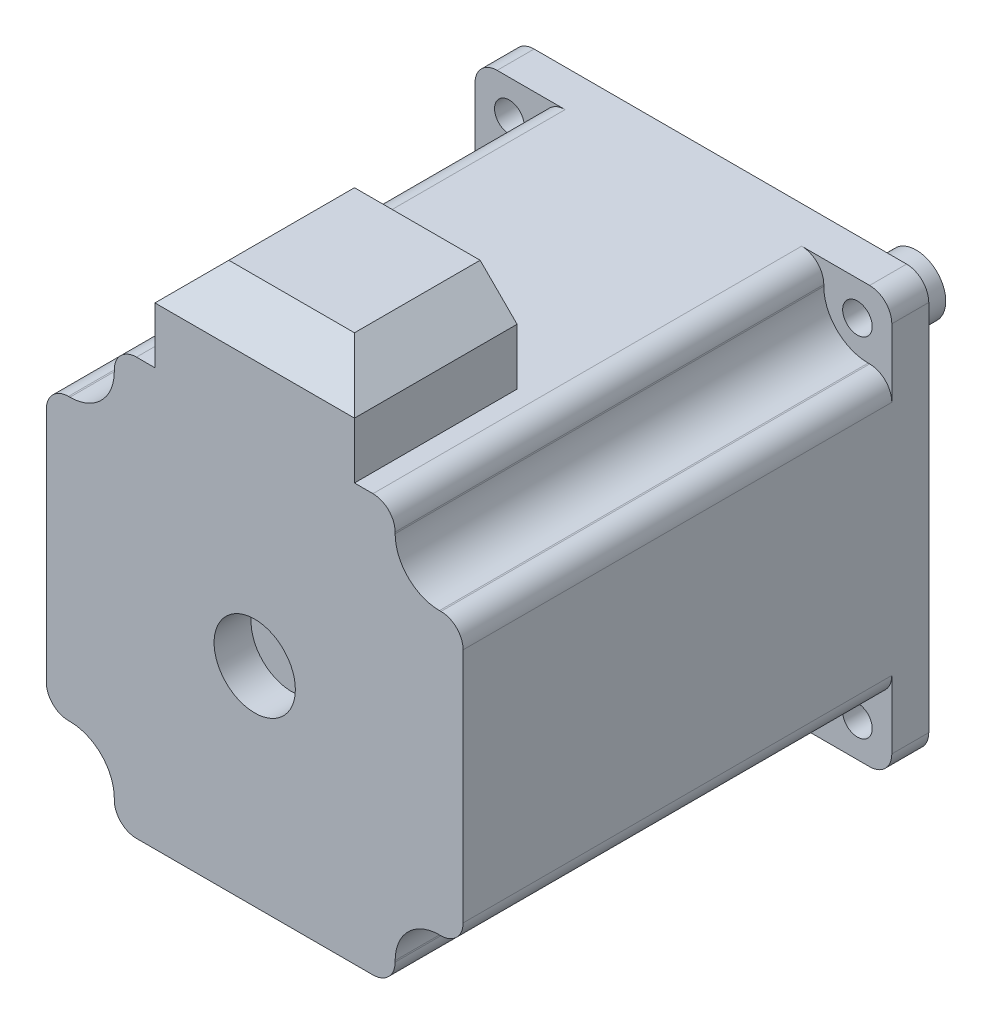
SolidWorks part; units mm, degrees
ref_plane "前视基准面" through (0, 0, 0) normal (0, 0, 1) x (1, 0, 0)
ref_plane "上视基准面" through (0, 0, 0) normal (0, 1, 0) x (1, 0, 0)
ref_plane "右视基准面" through (0, 0, 0) normal (1, 0, 0) x (0, 0, -1)
sketch "草图1" plane through (0, 0, 0) normal (0, 0, 1) x (1, 0, 0)
  line L1 (-28.2, 28.2) -> (28.2, 28.2)
  line L2 (-28.2, 28.2) -> (-28.2, -28.2)
  line L3 (-28.2, -28.2) -> (28.2, -28.2)
  line L4 (28.2, 28.2) -> (28.2, -28.2)
  line L5 (-28.2, 28.2) -> (28.2, -28.2) construction
  line L6 (-28.2, -28.2) -> (28.2, 28.2) construction
  point P0 (0, 0)
  dimension "D1" = 56.4
  dimension "D2" = 56.4
extrude "凸台-拉伸1" add sketch "草图1" along normal blind 63
sketch "草图2" plane through (0, 0, 0) normal (0, 0, -1) x (-1, 0, 0)
  line L0 (0, 0) -> (0, 23.55) construction
  line L1 (-23.55, 23.55) -> (23.55, 23.55) construction
  line L2 (-23.55, 23.55) -> (-23.55, -23.55) construction
  line L3 (-23.55, -23.55) -> (23.55, -23.55) construction
  line L4 (23.55, 23.55) -> (23.55, -23.55) construction
  circle A0 centre (23.55, 23.55) radius 2
  circle A1 centre (23.55, -23.55) radius 2
  circle A2 centre (-23.55, -23.55) radius 2
  circle A3 centre (-23.55, 23.55) radius 2
  point P0 (0, 0)
  dimension "D1" = 47.1
  dimension "D2" = 47.1
extrude "切除-拉伸1" cut sketch "草图2" against normal blind 63
sketch "草图3" plane through (0, 0, 63) normal (0, 0, 1) x (1, 0, 0)
  line L0 (28.2, -28.2) -> (28.2, 28.2) construction
  line L1 (-19, -28.2) -> (19, -28.2) construction
  line L2 (-19, -28.2) -> (-19, -19)
  line L3 (-19, 28.2) -> (19, 28.2) construction
  line L4 (19, -28.2) -> (19, -19)
  line L5 (-28.2, -19) -> (-28.2, -28.2)
  line L6 (-28.2, -28.2) -> (-19, -28.2)
  line L7 (-28.2, 19) -> (-19, 19)
  line L8 (-28.2, 19) -> (-28.2, -19) construction
  line L9 (-28.2, -19) -> (-19, -19)
  line L10 (28.2, 19) -> (28.2, -19) construction
  line L11 (28.2, -19) -> (28.2, -28.2)
  line L12 (28.2, -28.2) -> (19, -28.2)
  line L13 (19, 19) -> (28.2, 19)
  line L14 (19, 28.2) -> (28.2, 28.2)
  line L15 (-19, 19) -> (-19, 28.2)
  line L16 (19, 19) -> (19, 28.2)
  line L17 (28.2, 28.2) -> (28.2, 19)
  line L18 (19, -19) -> (28.2, -19)
  line L19 (-19, 28.2) -> (-28.2, 28.2)
  line L21 (-28.2, 28.2) -> (-28.2, 19)
  point P0 (0, 0)
  point P6 (0, 0)
  point P13 (-19, 19)
  point P14 (19, 19)
  point P15 (19, -19)
  point P16 (-19, -19)
  dimension "D1" = 38
  dimension "D2" = 9.2
  dimension "D3" = 38
extrude "切除-拉伸2" cut sketch "草图3" against normal blind 58
fillet "圆角1" radius 3 12 edges at (28.2, 19, 34) (19, 28.2, 34) (-28.2, 19, 34) (-19, 28.2, 34) (-19, -28.2, 34) (-28.2, -19, 34) (28.2, -19, 34) (19, -28.2, 34) (28.2, 28.2, 2.5) (-28.2, 28.2, 2.5) (-28.2, -28.2, 2.5) (28.2, -28.2, 2.5)
fillet "圆角2" radius 6 4 edges at (19, 19, 34) (19, -19, 34) (-19, -19, 34) (-19, 19, 34)
sketch "草图7" plane through (0, 0, 0) normal (0, 0, -1) x (-1, 0, 0)
  circle A0 centre (0, 0) radius 19
extrude "切除-拉伸4" cut sketch "草图7" against normal blind 20
sketch "草图4" plane through (0, 0, 0) normal (0, 0, -1) x (-1, 0, 0)
  circle A0 centre (0, 0) radius 19
extrude "凸台-拉伸2" add sketch "草图4" along normal blind 1.5
sketch "草图5" plane through (0, 0, -1.5) normal (0, 0, -1) x (-1, 0, 0)
  circle A0 centre (0, 0) radius 4
extrude "凸台-拉伸3" add sketch "草图5" along normal blind 25
sketch "草图8" plane through (0, 0, 63) normal (0, 0, 1) x (1, 0, 0)
  circle A0 centre (0, 0) radius 5.5
  dimension "D1" = 11
extrude "切除-拉伸5" cut sketch "草图8" against normal blind 5
sketch "草图11" plane through (0, 0, 63) normal (0, 0, 1) x (1, 0, 0)
  line L0 (0, 0) -> (0, 28.2) construction
  line L1 (16, 28.2) -> (-16, 28.2) construction
  line L2 (-13.5, 28.2) -> (13.5, 28.2)
  line L3 (-13.5, 40.8) -> (13.5, 40.8)
  line L4 (-13.5, 40.8) -> (-13.5, 28.2)
  line L6 (13.5, 40.8) -> (13.5, 28.2)
  dimension "D1" = 27
  dimension "D2" = 12.6
extrude "凸台-拉伸4" add sketch "草图11" against normal blind 22
chamfer "倒角3" distance 5 angle 45 3 edges at (13.5, 40.8, 52) (0, 40.8, 63) (-13.5, 40.8, 52)
